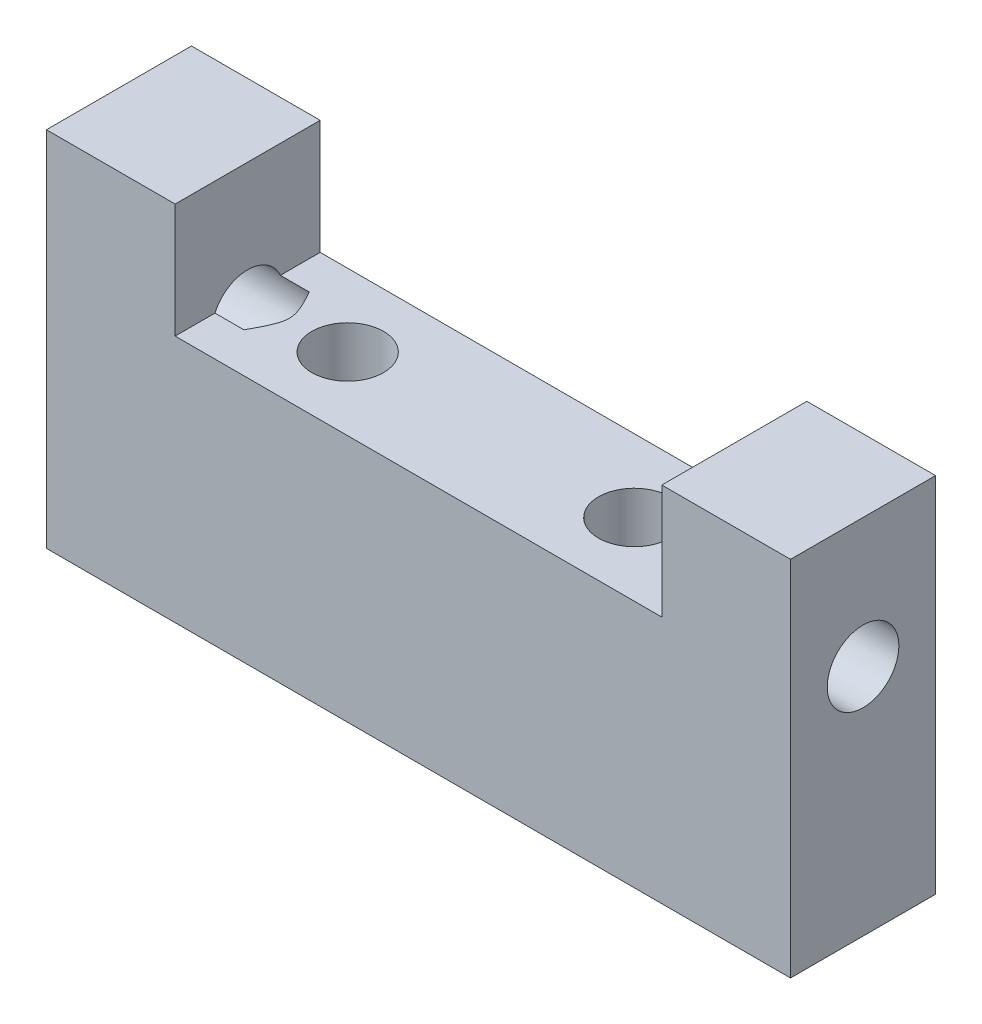
SolidWorks part; units mm, degrees
ref_plane "Piano frontale" through (0, 0, 0) normal (0, 0, 1) x (1, 0, 0)
ref_plane "Piano superiore" through (0, 0, 0) normal (0, 1, 0) x (1, 0, 0)
ref_plane "Piano destro" through (0, 0, 0) normal (1, 0, 0) x (0, 0, -1)
sketch "Schizzo1" plane through (0, 0, 0) normal (0, 0, 1) x (1, 0, 0)
  line L1 (-12.98, -6.325) -> (12.98, -6.325)
  line L2 (-12.98, -6.325) -> (-12.98, 6.325)
  line L3 (-12.98, 6.325) -> (12.98, 6.325)
  line L4 (12.98, -6.325) -> (12.98, 6.325)
  line L5 (-12.98, -6.325) -> (12.98, 6.325) construction
  line L6 (-12.98, 6.325) -> (12.98, -6.325) construction
  point P0 (0, 0)
  dimension "D1" = 12.65
  dimension "D2" = 25.96
extrude "Estrusione-Estrusione1" add sketch "Schizzo1" against normal blind 5.06
sketch "Schizzo2" plane through (0, 0, 0) normal (0, 0, 1) x (1, 0, 0)
  line L0 (0, 6.325) -> (0, -6.325) construction
  line L1 (-8.49, 6.325) -> (-8.49, 2.335)
  line L2 (-8.49, 2.335) -> (8.49, 2.335)
  line L3 (8.49, 6.325) -> (8.49, 2.335)
  line L4 (12.98, -6.325) -> (12.98, 6.325)
  line L5 (12.98, 6.325) -> (-12.98, 6.325)
  line L6 (-12.98, 6.325) -> (-12.98, -6.325)
  line L7 (-12.98, -6.325) -> (12.98, -6.325)
  line L8 (12.98, -6.325) -> (12.98, 6.325)
  line L9 (12.98, 6.325) -> (-12.98, 6.325)
  line L10 (-12.98, 6.325) -> (-12.98, -6.325)
  line L11 (-12.98, -6.325) -> (12.98, -6.325)
  point P11 (0, 2.335)
  line M6 (12.98, 6.325) -> (-12.98, 6.325)
  dimension "D2" = 16.98
  dimension "D3" = 8.66
  dimension "D1" = 0
extrude "Taglio-Estrusione1" cut sketch "Schizzo2" against normal through all contours L0 L9 L1 L2 | L0 L2 L3 M6
hole_wizard "Foro filettato M3x0.5-1" positions "Schizzo4" profile "Schizzo3" tap size "M3x0.5" standard "Ansi Metric" end condition through all
sketch "Schizzo4" plane through (0, 2.335, 0) normal (0, 1, 0) x (1, 0, 0)
  line L0 (0, 0) -> (0, 5.06) construction
  line L1 (-8.49, 0) -> (8.49, 0) construction
  line L2 (-8.49, 5.06) -> (8.49, 5.06) construction
  line L3 (-5, 2.53) -> (5, 2.53) construction
  point P0 (-5, 2.53)
  point P2 (5, 2.53)
  point P14 (0, 2.53)
  dimension "D1" = 10
sketch "Schizzo3" plane through (-5, 2.335, -2.53) normal (1, 0, 0) x (0, 0, 1)
  line L0 (0, 0) -> (0, 8.66)
  line L1 (0, 8.66) -> (1.25, 8.66)
  line L2 (1.25, 8.66) -> (1.25, 0)
  line L5 (1.25, 0) -> (0, 0)
  line L11 (0, -6.35) -> (0, 107.95) construction
  dimension "Thru Tap Drill Dia." = 2.5
  dimension "Thru Tap Drill Depth" = 8.66
cosmetic thread "Filettatura del foro1" parameters "D2"=3
cosmetic thread "Filettatura del foro2" parameters "D2"=3
hole_wizard "Foro filettato M3x0.5-2" positions "Schizzo6" profile "Schizzo5" tap size "M3x0.5" standard "Ansi Metric"
sketch "Schizzo6" plane through (-12.98, 0, 0) normal (-1, 0, 0) x (0, 0, 1)
  line L0 (-2.53, 1.825) -> (-2.53, 6.325) construction
  line L1 (-5.06, 6.325) -> (0, 6.325) construction
  point P0 (-2.53, 1.825)
  dimension "D1" = 4.5
sketch "Schizzo5" plane through (-12.98, 1.825, -2.53) normal (0, 1, 0) x (0, 0, 1)
  line L0 (0, 0) -> (0, 6.2511)
  line L1 (0, 6.2511) -> (1.25, 5.5)
  line L2 (1.25, 5.5) -> (1.25, 0)
  line L5 (1.25, 0) -> (0, 0)
  line L10 (0, 6.2511) -> (-1.25, 5.5) construction
  line L11 (0, -6.35) -> (0, 107.95) construction
  dimension "Tap Drill Dia." = 2.5
  dimension "Tap Drill Depth" = 5.5
  dimension "Drill Angle" = 118
cosmetic thread "Filettatura del foro3" parameters "D1"=5, "D2"=3
mirror "Specchia1" about plane through (0, 0, 0) normal (1, 0, 0) of "Foro filettato M3x0.5-2"
